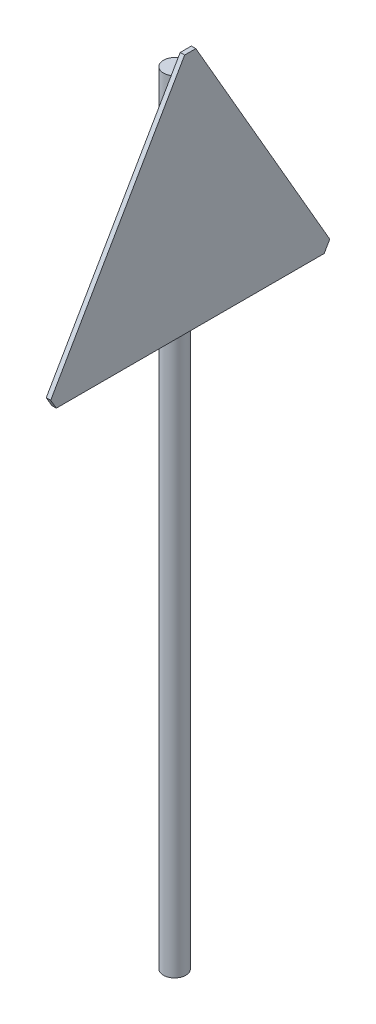
SolidWorks part; units mm, degrees
ref_plane "Спереди" through (0, 0, 0) normal (0, 0, 1) x (1, 0, 0)
ref_plane "Сверху" through (0, 0, 0) normal (0, 1, 0) x (1, 0, 0)
ref_plane "Справа" through (0, 0, 0) normal (1, 0, 0) x (0, 0, -1)
other "Configuration Table"
sketch "Sketch1" plane through (0, 0, 0) normal (0, 1, 0) x (1, 0, 0)
  circle A0 centre (0, 0) radius 0.5
  dimension "D1" = 1
extrude "Boss-Extrude1" add sketch "Sketch1" along normal blind 35
ref_plane "Plane1" through (0.5, 0, 0) normal (1, 0, 0) x (0, 0, -1)
sketch "Sketch2" plane through (0.5, 0, 0) normal (1, 0, 0) x (0, 0, -1)
  line L0 (0, 35) -> (0, 36.3584)
  line L1 (0.5, 35) -> (-0.5, 35) construction
  line L2 (6.5, 25.1001) -> (0, 36.3584)
  line L3 (0, 36.3584) -> (-6.5, 25.1001)
  line L4 (-6.5, 25.1001) -> (6.5, 25.1001)
  dimension "D1" = 60
  dimension "D2" = 60
  dimension "D3" = 13
extrude "Boss-Extrude2" add sketch "Sketch2" along normal blind 0.2 separate body
chamfer "Chamfer1" distance 0.5 angle 60 2 edges at (0.6, 25.1001, -6.5) (0.6, 25.1001, 6.5)
chamfer "Chamfer2" distance 0.5 angle 60 1 edges at (0.6, 36.3584, 0)
